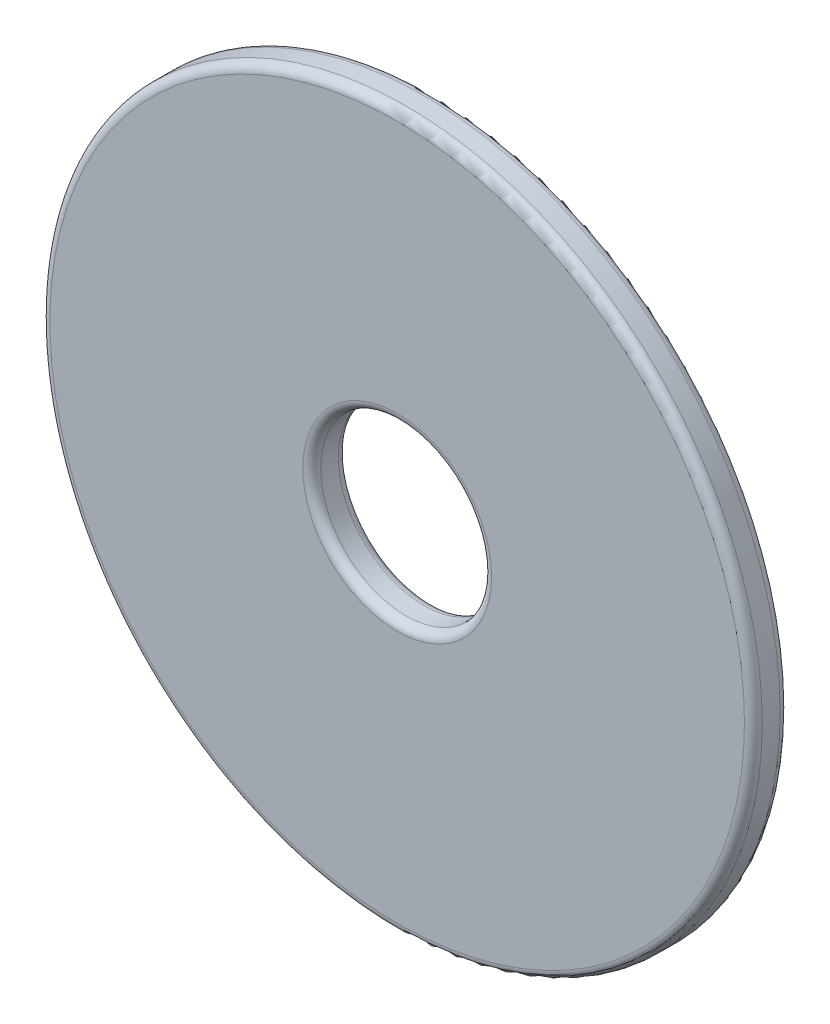
SolidWorks part; units mm, degrees
material "Wrought Stainless Steel"
ref_plane "Front Plane" through (0, 0, 0) normal (0, 0, 1) x (1, 0, 0)
ref_plane "Top Plane" through (0, 0, 0) normal (0, 1, 0) x (1, 0, 0)
ref_plane "Right Plane" through (0, 0, 0) normal (1, 0, 0) x (0, 0, -1)
sketch "Sketch1" plane through (0, 0, 0) normal (0, 0, 1) x (1, 0, 0)
  circle A0 centre (0, 0) radius 15.875
  circle A1 centre (0, 0) radius 3.81
  dimension "D1" = 31.75
  dimension "D2" = 7.62
extrude "Boss-Extrude1" add sketch "Sketch1" along normal blind 1.5875
fillet "Fillet1" radius 0.3969 4 edges at (3.81, 0, 0) (15.875, 0, 0) (3.81, 0, 1.5875) (15.875, 0, 1.5875)
